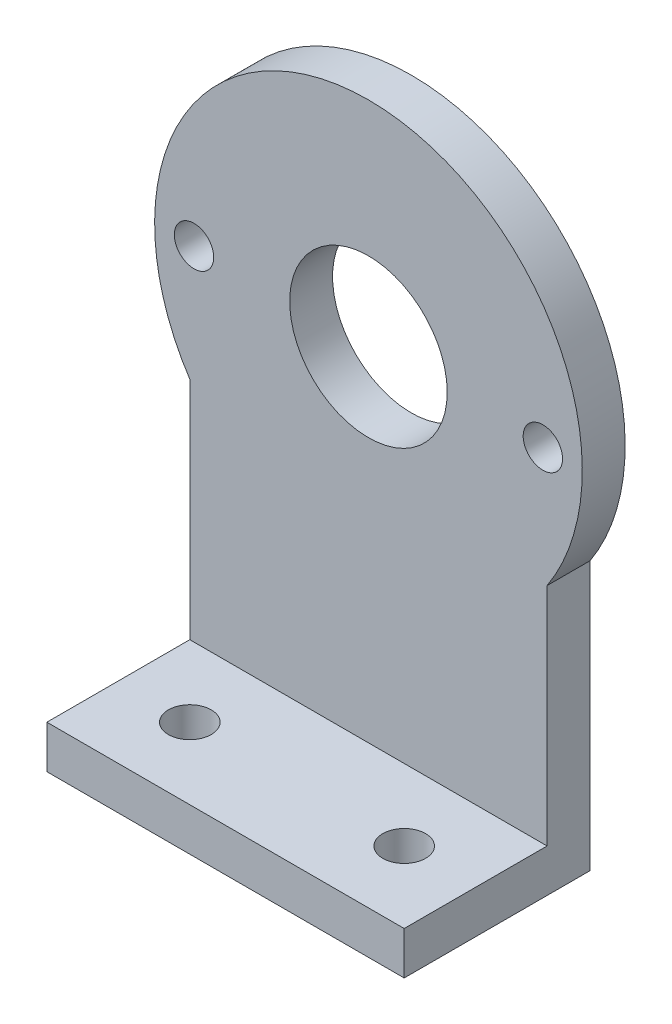
SolidWorks part; units mm, degrees
ref_plane "Front Plane" through (0, 0, 0) normal (0, 0, 1) x (1, 0, 0)
ref_plane "Top Plane" through (0, 0, 0) normal (0, 1, 0) x (1, 0, 0)
ref_plane "Right Plane" through (0, 0, 0) normal (1, 0, 0) x (0, 0, -1)
sketch "Sketch1" plane through (0, 0, 0) normal (0, 0, 1) x (1, 0, 0)
  line L1 (-15.875, -10.4396) -> (15.875, -10.4396)
  line L2 (-15.875, -10.4396) -> (-15.875, -34.29)
  line L3 (-15.875, -34.29) -> (15.875, -34.29)
  line L4 (15.875, -10.4396) -> (15.875, -34.29)
  circle A0 centre (0, 0) radius 19
  arc A2 (-15.875, -10.4396) -> (15.875, -10.4396) centre (0, 0) ccw
  dimension "D1" = 38
  dimension "D2" = 34.29
  dimension "D3" = 31.75
extrude "Boss-Extrude1" add sketch "Sketch1" along normal blind 3.81
sketch "Sketch3" plane through (0, 0, 3.81) normal (0, 0, 1) x (1, 0, 0)
  circle A0 centre (0, 0) radius 7
  dimension "D1" = 14
extrude "Cut-Extrude1" cut sketch "Sketch3" against normal through all
sketch "Sketch4" plane through (0, 0, 3.81) normal (0, 0, 1) x (1, 0, 0)
  line L0 (15.875, -10.4396) -> (15.875, -34.29) construction
  line L1 (-15.875, -34.29) -> (15.875, -34.29)
  line L2 (-15.875, -34.29) -> (-15.875, -30.48)
  line L3 (-15.875, -30.48) -> (15.875, -30.48)
  line L4 (15.875, -34.29) -> (15.875, -30.48)
  dimension "D1" = 3.81
extrude "Boss-Extrude2" add sketch "Sketch4" along normal blind 12.7
sketch "Sketch5" plane through (0, -30.48, 0) normal (0, 1, 0) x (1, 0, 0)
  line L0 (-15.875, -10.16) -> (15.875, -10.16) construction
  line L1 (-15.875, -16.51) -> (-15.875, -3.81) construction
  line L2 (15.875, -16.51) -> (15.875, -3.81) construction
  line L3 (0, -3.81) -> (0, -16.51) construction
  line L4 (15.875, -3.81) -> (-15.875, -3.81) construction
  line L5 (15.875, -16.51) -> (-15.875, -16.51) construction
  circle A0 centre (-9.525, -10.16) radius 1.905
  circle A1 centre (9.525, -10.16) radius 1.905
  dimension "D1" = 3.81
  dimension "D2" = 9.525
extrude "Cut-Extrude2" cut sketch "Sketch5" against normal through all
sketch "Sketch6" plane through (0, 0, 3.81) normal (0, 0, 1) x (1, 0, 0)
  line L0 (0, 19) -> (0, -30.48) construction
  line L1 (15.875, -30.48) -> (-15.875, -30.48) construction
  circle A0 centre (0, 0) radius 15.5 construction
  circle A1 centre (15.5, 0) radius 1.75
  arc A2 (15.875, -10.4396) -> (-15.875, -10.4396) centre (0, 0) ccw construction
  circle A3 centre (-15.5, 0) radius 1.75
  dimension "D1" = 31
  dimension "D2" = 3.5
extrude "Cut-Extrude3" cut sketch "Sketch6" against normal through all
